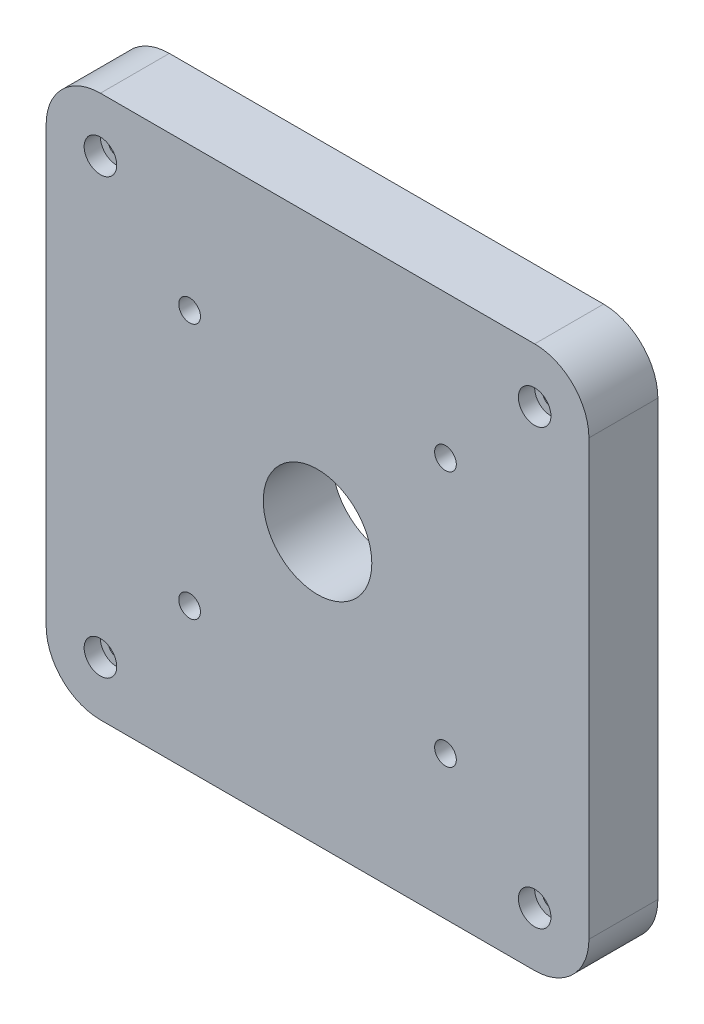
SolidWorks part; units mm, degrees
ref_plane "Front Plane" through (0, 0, 0) normal (0, 0, 1) x (1, 0, 0)
ref_plane "Top Plane" through (0, 0, 0) normal (0, 1, 0) x (1, 0, 0)
ref_plane "Right Plane" through (0, 0, 0) normal (1, 0, 0) x (0, 0, -1)
sketch "Croquis1" plane through (0, 0, 0) normal (0, 0, 1) x (1, 0, 0)
  line L1 (10, 0) -> (90, 0)
  line L2 (0, 10) -> (0, 90)
  line L3 (10, 100) -> (90, 100)
  line L4 (100, 10) -> (100, 90)
  arc A0 (90, 100) -> (100, 90) centre (90, 90) cw
  arc A1 (90, 0) -> (100, 10) centre (90, 10) ccw
  arc A2 (10, 0) -> (0, 10) centre (10, 10) cw
  arc A3 (0, 90) -> (10, 100) centre (10, 90) cw
  point P11 (0, 0)
  dimension "D1" = 10
extrude "Saliente-Extruir1" add sketch "Croquis1" along normal blind 12.7
sketch "Croquis2" plane through (0, 0, 12.7) normal (0, 0, 1) x (1, 0, 0)
  line L0 (0, 90) -> (0, 10) construction
  line L1 (10, 0) -> (90, 0) construction
  line L2 (90, 100) -> (10, 100) construction
  line L3 (100, 10) -> (100, 90) construction
  circle A0 centre (10, 90) radius 3
  circle A1 centre (10, 10) radius 3
  circle A2 centre (90, 90) radius 3
  circle A3 centre (90, 10) radius 3
  dimension "D1" = 10
  dimension "D2" = 10
  dimension "D3" = 10
  dimension "D4" = 10
  dimension "D5" = 10
  dimension "D6" = 10
  dimension "D7" = 10
  dimension "D8" = 10
extrude "Cortar-Extruir1" cut sketch "Croquis2" against normal blind 3
sketch "Croquis3" plane through (0, 0, 12.7) normal (0, 0, 1) x (1, 0, 0)
  line L1 (90, 100) -> (10, 100) construction
  line L2 (100, 10) -> (100, 90) construction
  circle A5 centre (50, 50) radius 10
  circle A6 centre (26.43, 73.57) radius 2
  circle A7 centre (73.57, 73.57) radius 2
  circle A8 centre (26.43, 26.43) radius 2
  circle A9 centre (73.57, 26.43) radius 2
  dimension "D1" = 47.14
  dimension "D7" = 50
  dimension "D8" = 50
  dimension "D2" = 47.14
  dimension "D3" = 47.14
  dimension "D4" = 47.14
  dimension "D5" = 23.57
  dimension "D6" = 23.57
extrude "Cortar-Extruir2" cut sketch "Croquis3" against normal blind 31
sketch "Croquis4" plane through (0, 0, 9.7) normal (0, 0, 1) x (1, 0, 0)
  circle A0 centre (10, 90) radius 1.5
  circle A1 centre (90, 90) radius 1.5
  circle A2 centre (90, 10) radius 1.5
  circle A3 centre (10, 10) radius 1.5
extrude "Cortar-Extruir3" cut sketch "Croquis4" against normal blind 31
sketch "Croquis5" plane through (0, 0, 0) normal (0, 0, -1) x (-1, 0, 0)
  circle A0 centre (-73.57, 73.57) radius 4
  circle A1 centre (-26.43, 73.57) radius 4
  circle A2 centre (-26.43, 26.43) radius 4
  circle A3 centre (-73.57, 26.43) radius 4
extrude "Cortar-Extruir4" cut sketch "Croquis5" against normal blind 3
